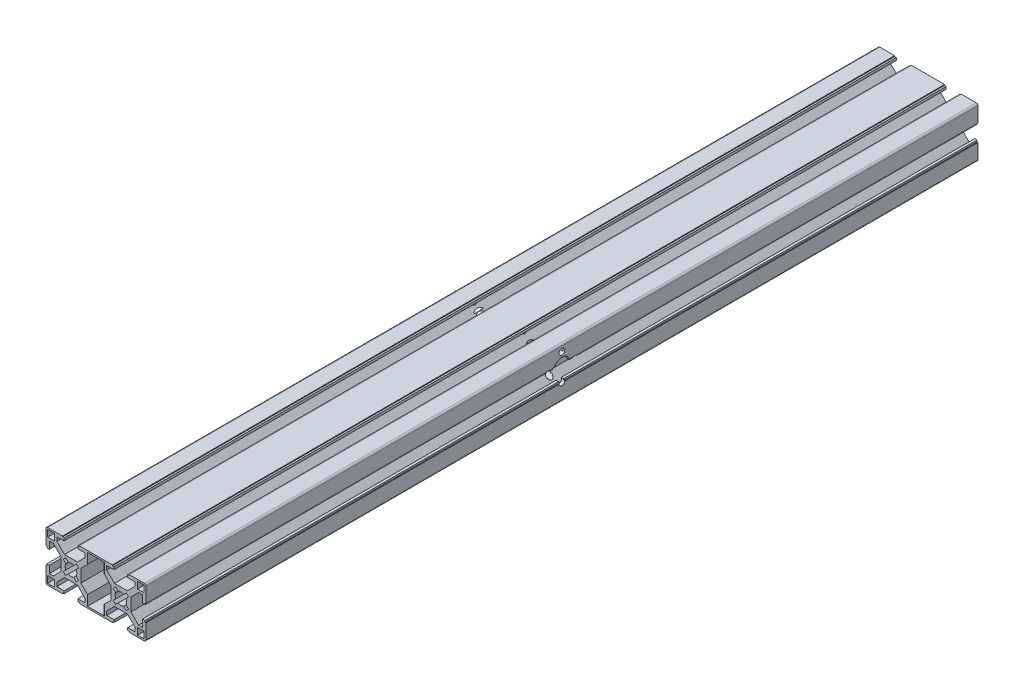
SolidWorks part; units mm, degrees
material "6063-O"
ref_plane "Plano frontal" through (0, 0, 0) normal (0, 0, 1) x (1, 0, 0)
ref_plane "Plano superior" through (0, 0, 0) normal (0, 1, 0) x (1, 0, 0)
ref_plane "Plano direito" through (0, 0, 0) normal (1, 0, 0) x (0, 0, -1)
sketch "Esboço1" plane through (0, 0, 0) normal (0, 0, 1) x (1, 0, 0)
  line L5 (0, 0) -> (-17.7944, 17.7944) construction
  line L6 (0, 3.5) -> (0, 6)
  line L8 (0, 6) -> (-3.8787, 6)
  line L9 (-3.5, 0) -> (-6, 0)
  line L48 (-6, 0) -> (-6, 3.8787)
  line L49 (-3.8787, 6) -> (-8.5, 10.6213)
  line L50 (-6, 3.8787) -> (-10.6213, 8.5)
  line L51 (0, 0) -> (-12.921, 0) construction
  line L52 (-8.5, 13) -> (-4.1, 13)
  line L53 (-4.1, 13) -> (-4.1, 14.5)
  line L54 (-4.1, 14.5) -> (-5.1, 14.5)
  line L55 (-5.1, 14.5) -> (-5.1, 15)
  line L56 (-5.1, 15) -> (-15, 15)
  line L57 (-15, 5.1) -> (-15, 15)
  line L58 (-14.5, 5.1) -> (-15, 5.1)
  line L59 (-14.5, 4.1) -> (-14.5, 5.1)
  line L60 (-13, 4.1) -> (-14.5, 4.1)
  line L61 (-13, 8.5) -> (-13, 4.1)
  line L62 (-1.6646, 3.0788) -> (-3.182, 4.5962)
  line L63 (-3.0788, 1.6646) -> (-4.5962, 3.182)
  line L64 (-4.5962, 3.182) -> (-3.182, 4.5962)
  line L65 (-8.5, 13) -> (-8.5, 10.6213)
  line L66 (-10, 14) -> (-14, 14)
  line L67 (-10, 14) -> (-10, 10)
  line L68 (-10, 10) -> (-14, 10)
  line L69 (-14, 14) -> (-14, 10)
  line L70 (-10, 14) -> (-14, 10) construction
  line L71 (-10, 10) -> (-14, 14) construction
  line L72 (-13, 8.5) -> (-10.6213, 8.5)
  circle A1 centre (0, 0) radius 3.5
  point P25 (-12, 12)
  dimension "D5" = 10.9
  dimension "D9" = 5.5
  dimension "D10" = 2
  dimension "D11" = 4
  dimension "D12" = 4
  dimension "D13" = 1
  dimension "D1" = 7
  dimension "D2" = 6
  dimension "D3" = 3
  dimension "D4" = 9.9
  dimension "D6" = 0.5
  dimension "D7" = 1.5
  dimension "D8" = 15
  dimension "D14" = 6.5
extrude "Ressalto-extrusão1" add sketch "Esboço1" along normal blind 500 contours A1 L6 L8 L49 L65 L52 L53 L54 L55 L56 L57 L58 L59 L60 L61 L72 L50 L48 L9 L63 L64 L62 L69 L66 L67 L68
sketch "Esboço3" plane through (0, 0, 0) normal (1, 0, 0) x (0, 0, -1)
  line L0 (0, 0) -> (-1000, 0) construction
  dimension "D1" = 1000
pattern_circular "PadrãoCircular1" count 4 over 360 about axis through (0, 0, 0) along (0, 0, 1) of "Ressalto-extrusão1"
pattern_linear "Padrão linear1" count 2 spacing 30 along (1, 0, 0) of "Ressalto-extrusão1", "PadrãoCircular1"
sketch "Esboço4" plane through (0, 0, 0) normal (0, 0, -1) x (-1, 0, 0)
  line L0 (-20, 14) -> (-20, -14)
  line L1 (-20, -14) -> (-10, -14)
  line L2 (-10, -14) -> (-10, 14)
  line L3 (-10, 14) -> (-20, 14)
extrude "Corte-extrusão1" cut sketch "Esboço4" against normal through all
fillet "Filete1" radius 1 4 edges at (45, -15, 250) (45, 15, 250) (-15, 15, 250) (-15, -15, 250)
ref_plane "Plane1" through (0, 0, 250) normal (0, 0, -1) x (-1, 0, 0)
ref_plane "Plane2" through (15, 0, 0) normal (-1, 0, 0) x (0, 0, 1)
sketch "Sketch1" plane through (-15, 0, 0) normal (-1, 0, 0) x (0, 0, 1)
  line L0 (250, 14) -> (250, -14) construction
  line L3 (500, 14) -> (0, 14) construction
  line L4 (0, -14) -> (500, -14) construction
  line L5 (500, -15) -> (0, -15) construction
  circle A0 centre (250, 3) radius 5.1
  point P8 (0, 0)
  point P9 (250, 6.452)
  dimension "D1" = 10.2
  dimension "D2" = 18
extrude "Cut-Extrude1" cut sketch "Sketch1" against normal blind 10
mirror "Mirror1" about plane through (15, 0, 0) normal (-1, 0, 0) of "Cut-Extrude1"
sketch "Sketch2" plane through (-15, 0, 0) normal (-1, 0, 0) x (0, 0, 1)
  line L0 (250, 14) -> (250, -14) construction
  line L1 (500, 14) -> (0, 14) construction
  line L2 (0, -14) -> (500, -14) construction
  line L3 (500, -15) -> (0, -15) construction
  circle A0 centre (250, 3) radius 4
  circle A1 centre (250, 11) radius 1.75
  circle A2 centre (258, 3) radius 1.75
  circle A3 centre (250, -5) radius 1.75
  circle A4 centre (242, 3) radius 1.75
  point P10 (0, 0)
  point P11 (0, 0)
  point P12 (250, 2.2589)
  point P19 (250, 3)
  dimension "D1" = 8
  dimension "D2" = 3.5
  dimension "D4" = 16
  dimension "D5" = 18
  dimension "D3" = 4
extrude "Cut-Extrude2" cut sketch "Sketch2" against normal through all
